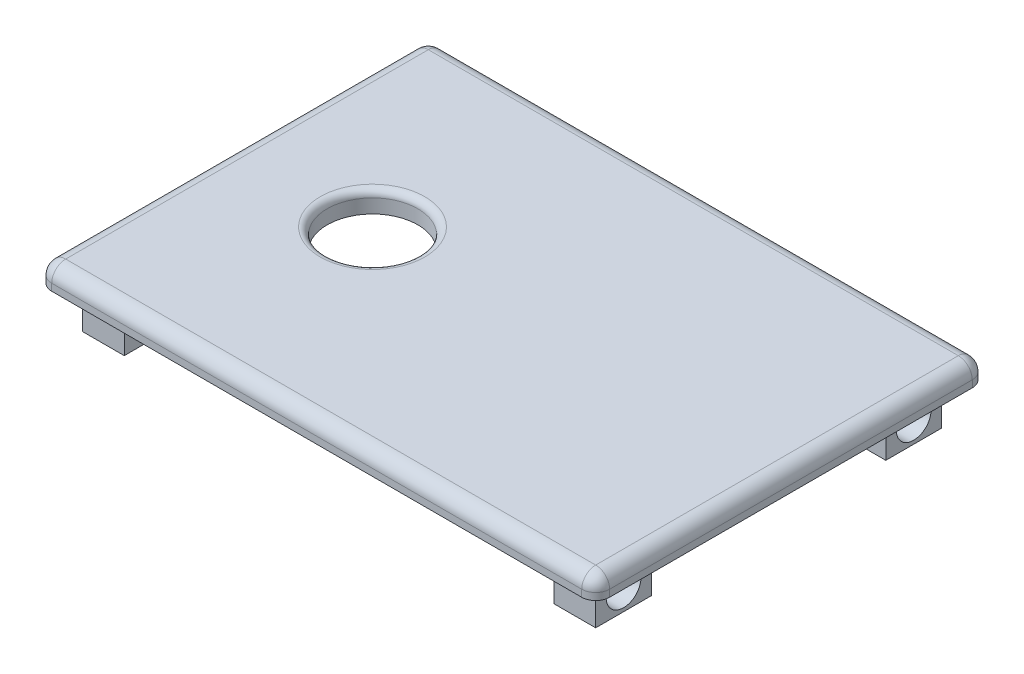
SolidWorks part; units mm, degrees
ref_plane "Front Plane" through (0, 0, 0) normal (0, 0, 1) x (1, 0, 0)
ref_plane "Top Plane" through (0, 0, 0) normal (0, 1, 0) x (1, 0, 0)
ref_plane "Right Plane" through (0, 0, 0) normal (1, 0, 0) x (0, 0, -1)
sketch "Sketch1" plane through (0, 0, 0) normal (0, 1, 0) x (1, 0, 0)
  line L1 (-47.8861, 42.6395) -> (28.1139, 42.6395)
  line L2 (-49.8861, 40.6395) -> (-49.8861, -11.3605)
  line L3 (-47.8861, -13.3605) -> (28.1139, -13.3605)
  line L4 (30.1139, 40.6395) -> (30.1139, -11.3605)
  arc A0 (28.1139, -13.3605) -> (30.1139, -11.3605) centre (28.1139, -11.3605) ccw
  arc A1 (28.1139, 42.6395) -> (30.1139, 40.6395) centre (28.1139, 40.6395) cw
  arc A2 (-47.8861, 42.6395) -> (-49.8861, 40.6395) centre (-47.8861, 40.6395) ccw
  arc A3 (-49.8861, -11.3605) -> (-47.8861, -13.3605) centre (-47.8861, -11.3605) ccw
  circle A17 centre (-29.8861, 14.6395) radius 6.5
  point P0 (0, 0)
  point P3 (0, 0)
  point P4 (-49.8861, 14.6395)
  dimension "D3" = 2
  dimension "D2" = 13
  dimension "D4" = 20
  dimension "D12" = 80
  dimension "D13" = 56
extrude "Boss-Extrude1" add sketch "Sketch1" along normal blind 3
fillet "Fillet1" radius 2 8 edges at (-49.3003, 3, 12.7747) (-49.8861, 3, -14.6395) (-49.3003, 3, -42.0537) (-9.8861, 3, -42.6395) (29.5281, 3, -42.0537) (30.1139, 3, -14.6395) (29.5281, 3, 12.7747) (-9.8861, 3, 13.3605)
sketch "Sketch3" plane through (0, 0, 0) normal (0, -1, 0) x (1, 0, 0)
  line L4 (26.1139, 9.3605) -> (-45.8861, 9.3605)
  line L5 (-45.8861, 9.3605) -> (-45.8861, -38.6395)
  line L6 (-45.8861, -38.6395) -> (26.1139, -38.6395)
  line L7 (26.1139, -38.6395) -> (26.1139, 9.3605)
  line L8 (27.1139, 10.3605) -> (-46.8861, 10.3605)
  line L9 (-46.8861, 10.3605) -> (-46.8861, -39.6395)
  line L10 (-46.8861, -39.6395) -> (27.1139, -39.6395)
  line L11 (27.1139, -39.6395) -> (27.1139, 10.3605)
  line L12 (27.1139, 10.3605) -> (-46.8861, 10.3605)
  line L13 (-46.8861, 10.3605) -> (-46.8861, -39.6395)
  line L14 (-46.8861, -39.6395) -> (27.1139, -39.6395)
  line L15 (27.1139, -39.6395) -> (27.1139, 10.3605)
  dimension "D1" = 3
  dimension "D2" = 1
extrude "Boss-Extrude2" add sketch "Sketch3" along normal blind 3
sketch "Sketch4" plane through (0, -3, 0) normal (0, -1, 0) x (1, 0, 0)
  line L0 (-46.8861, -39.6395) -> (27.1139, -39.6395) construction
  line L1 (27.1139, -39.6395) -> (27.1139, 10.3605) construction
  line L2 (27.1139, 10.3605) -> (-46.8861, 10.3605) construction
  line L3 (-46.8861, 10.3605) -> (-46.8861, -39.6395) construction
  line L4 (-46.8861, -39.6395) -> (27.1139, -39.6395)
  line L5 (27.1139, -39.6395) -> (27.1139, 10.3605)
  line L6 (27.1139, 10.3605) -> (-46.8861, 10.3605)
  line L7 (-46.8861, 10.3605) -> (-46.8861, -39.6395)
  line L8 (-46.6861, 10.1605) -> (-46.6861, -39.4395)
  line L9 (-46.6861, -39.4395) -> (26.9139, -39.4395)
  line L10 (26.9139, -39.4395) -> (26.9139, 10.1605)
  line L11 (26.9139, 10.1605) -> (-46.6861, 10.1605)
  dimension "D1" = 0.2
extrude "Cut-Extrude1" cut sketch "Sketch4" against normal up to surface (3 mm away) up to face at (-9.8861, 0, -14.6395)
fillet "Fillet2" radius 1 1 edges at (-29.8861, 3, -8.1395)
sketch "Sketch6" plane through (0, 0, 0) normal (0, -1, 0) x (1, 0, 0)
  line L0 (-9.8861, 9.3605) -> (-9.8861, -38.6395) construction
  line L1 (-46.6861, 10.1605) -> (-40.6861, 10.1605)
  line L2 (-46.6861, 10.1605) -> (-46.6861, 2.1605)
  line L3 (-46.6861, 2.1605) -> (-40.6861, 2.1605)
  line L4 (-40.6861, 10.1605) -> (-40.6861, 2.1605)
  line L5 (26.1139, 9.3605) -> (-45.8861, 9.3605) construction
  line L6 (-45.8861, -38.6395) -> (26.1139, -38.6395) construction
  line L7 (-45.8861, -14.6395) -> (26.1139, -14.6395) construction
  line L8 (-45.8861, 9.3605) -> (-45.8861, -38.6395) construction
  line L9 (26.1139, -38.6395) -> (26.1139, 9.3605) construction
  line L10 (26.9139, 2.1605) -> (20.9139, 2.1605)
  line L11 (20.9139, 10.1605) -> (20.9139, 2.1605)
  line L12 (26.9139, 10.1605) -> (20.9139, 10.1605)
  line L13 (26.9139, 10.1605) -> (26.9139, 2.1605)
  line L14 (26.9139, -39.4395) -> (26.9139, -31.4395)
  line L15 (26.9139, -39.4395) -> (20.9139, -39.4395)
  line L16 (20.9139, -39.4395) -> (20.9139, -31.4395)
  line L17 (26.9139, -31.4395) -> (20.9139, -31.4395)
  line L18 (-46.6861, -31.4395) -> (-40.6861, -31.4395)
  line L19 (-40.6861, -39.4395) -> (-40.6861, -31.4395)
  line L20 (-46.6861, -39.4395) -> (-40.6861, -39.4395)
  line L21 (-46.6861, -39.4395) -> (-46.6861, -31.4395)
  dimension "D1" = 8
  dimension "D2" = 6
extrude "Boss-Extrude3" add sketch "Sketch6" along normal blind 6
sketch "Sketch7" plane through (-46.6861, 0, 0) normal (-1, 0, 0) x (0, 0, 1)
  line L0 (-31.4395, -6) -> (-39.4395, -6) construction
  line L2 (10.1605, -6) -> (2.1605, -6) construction
  circle A0 centre (-35.4395, -3) radius 2.5
  circle A1 centre (6.1605, -3) radius 2.5
  point P0 (0, 0)
  point P7 (-35.4395, -6)
  point P16 (6.1605, -6)
  dimension "D1" = 5
  dimension "D2" = 5
  dimension "D3" = 3
  dimension "D4" = 3
extrude "Cut-Extrude2" cut sketch "Sketch7" against normal through all
